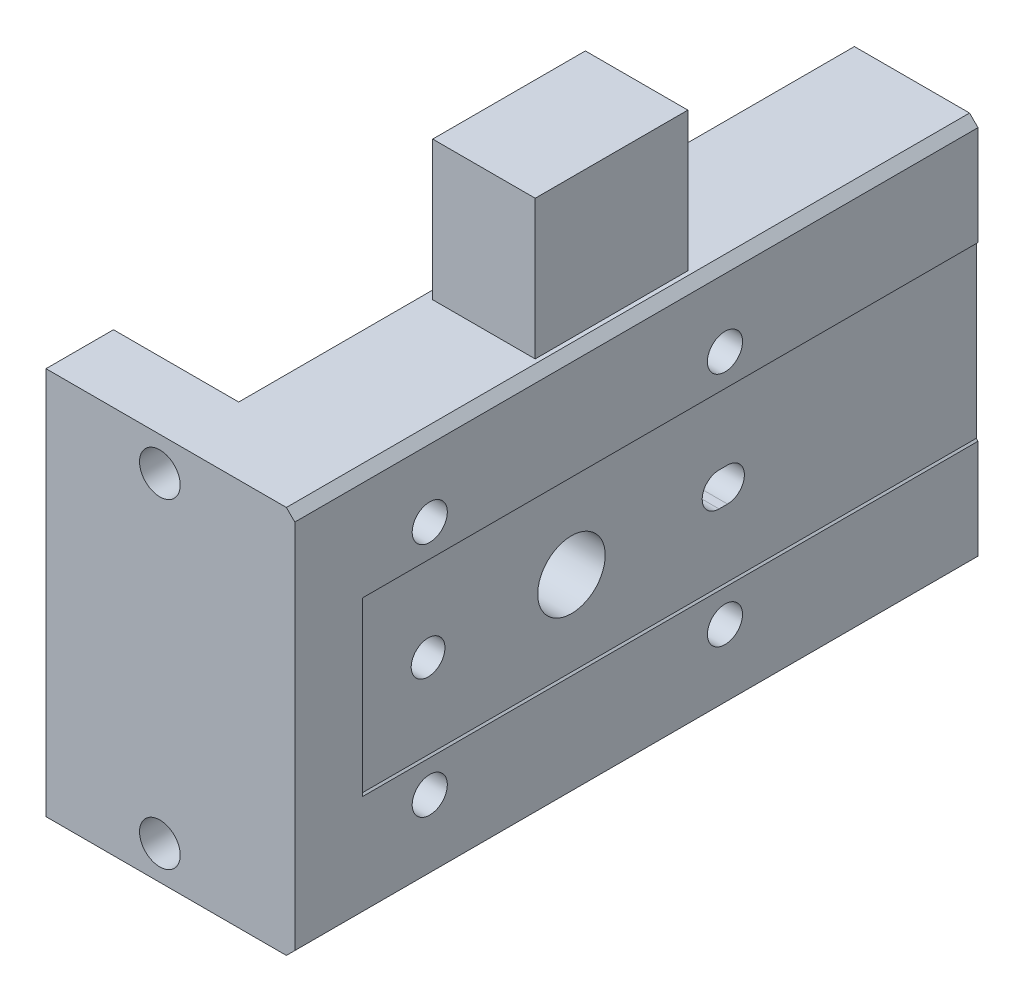
SolidWorks part; units mm, degrees
ref_plane "Front" through (0, 0, 0) normal (0, 0, 1) x (1, 0, 0)
ref_plane "Top" through (0, 0, 0) normal (0, 1, 0) x (1, 0, 0)
ref_plane "Right" through (0, 0, 0) normal (1, 0, 0) x (0, 0, -1)
sketch "Sketch1" plane through (0, 0, -1048.9574) normal (0, 0, 1) x (1, 0, 0)
  line L0 (8.0391, 23) -> (-8.0391, 23) construction
  line L1 (-6.1741, 23) -> (23.3259, 23)
  line L2 (-6.1741, 23) -> (-6.1741, -23)
  line L3 (-6.1741, -23) -> (23.3259, -23)
  line L4 (23.3259, 23) -> (23.3259, 10.2)
  line L5 (-6.1741, 0) -> (23.1259, 0) construction
  line L6 (-8.6741, 22.365) -> (-8.6741, 8.135) construction
  line L8 (-1.4859, -23) -> (1.4859, -23) construction
  line L9 (23.1259, 10) -> (23.1259, -10)
  line L10 (23.1259, -10) -> (23.3259, -10.2)
  line L11 (23.1259, 10) -> (23.3259, 10.2)
  line L12 (23.3259, -10.2) -> (23.3259, -23)
  dimension "D1" = 2.5
  dimension "D2" = 32
  dimension "D3" = 45
  dimension "D4" = 0.2
  dimension "D5" = 20
extrude "Base-Extrude" add sketch "Sketch1" along normal up to surface (8 mm away)
sketch "Sketch3" plane through (0, 0, -1048.9574) normal (0, 0, -1) x (-1, 0, 0)
  line L0 (-23.3259, 10.2) -> (-23.3259, 23) construction
  line L1 (-23.3259, 23) -> (6.1741, 23) construction
  line L2 (-23.3259, 10.2) -> (-23.3259, 23)
  line L3 (-23.3259, 23) -> (-8.6741, 23)
  line L4 (6.1741, -23) -> (-23.3259, -23) construction
  line L5 (-23.3259, -23) -> (-23.3259, -10.2) construction
  line L6 (-23.3259, -10.2) -> (-23.1259, -10) construction
  line L7 (-23.1259, -10) -> (-23.1259, 10) construction
  line L8 (-23.1259, 10) -> (-23.3259, 10.2) construction
  line L9 (-8.6741, -23) -> (-23.3259, -23)
  line L10 (-23.3259, -23) -> (-23.3259, -10.2)
  line L11 (-23.3259, -10.2) -> (-23.1259, -10)
  line L12 (-23.1259, -10) -> (-23.1259, 10)
  line L13 (-23.1259, 10) -> (-23.3259, 10.2)
  line L14 (-8.6741, -8.135) -> (-8.6741, -22.365) construction
  line L19 (-8.6741, 23) -> (-8.6741, -23)
extrude "Boss-Extrude1" add sketch "Sketch3" along normal up to surface (73 mm away)
sketch "Sketch15" plane through (0, 0, -1040.9574) normal (0, 0, 1) x (1, 0, 0)
  line L0 (23.1259, -10) -> (23.1259, 10) construction
  line L1 (23.1259, -10) -> (23.1259, 10)
  line L2 (23.3259, -10.2) -> (23.1259, -10) construction
  line L3 (23.1259, 10) -> (23.3259, 10.2) construction
  line L4 (23.3259, -10.2) -> (23.1259, -10)
  line L5 (23.1259, 10) -> (23.3259, 10.2)
  line L6 (23.3259, -10.2) -> (23.3259, 10.2)
extrude "Boss-Extrude3" add sketch "Sketch15" against normal up to surface (8 mm away) up to face at (1.25, -5.75, -1048.9574)
hole_wizard "8.0 Diameter Hole1" positions "Sketch5" profile "Sketch4" hole size "M8.0" standard "Ansi Metric" end condition through all
sketch "Sketch5" plane through (23.1259, 0, 0) normal (1, 0, 0) x (0, 0, -1)
  point P0 (1073.9574, 0)
sketch "Sketch4" plane through (23.1259, 0, -1073.9574) normal (0, 1, 0) x (0, 0, -1)
  line L0 (0, 0) -> (0, 29.3)
  line L1 (0, 29.3) -> (4, 29.3)
  line L2 (4, 29.3) -> (4, 0)
  line L5 (4, 0) -> (0, 0)
  line L11 (0, -6.35) -> (0, 107.95) construction
  dimension "Thru Hole Dia." = 8
  dimension "Thru Hole Depth" = 29.3
hole_wizard "#8-32 Tapped Hole1" positions "Sketch7" profile "Sketch6" tap size "#8-32" standard "Ansi Inch"
sketch "Sketch7" plane through (23.3259, 0, 0) normal (1, 0, 0) x (0, 0, -1)
  point P0 (1056.9574, 14)
  point P1 (1091.9574, 14)
  point P3 (1056.9574, -14)
  point P4 (1091.9574, -14)
sketch "Sketch6" plane through (23.3259, 14, -1056.9574) normal (0, 1, 0) x (0, 0, -1)
  line L0 (0, 0) -> (0, 13.3314)
  line L1 (0, 13.3314) -> (1.7272, 12.2936)
  line L2 (1.7272, 12.2936) -> (1.7272, 8.3312)
  line L3 (1.7272, 8.3312) -> (2.0828, 8.3312)
  line L4 (2.0828, 8.3312) -> (2.0828, 0)
  line L5 (2.0828, 0) -> (0, 0)
  line L10 (0, 13.3314) -> (-1.7272, 12.2936) construction
  line L11 (0, -6.35) -> (0, 107.95) construction
  dimension "Tap Drill Dia." = 3.4544
  dimension "Tap Drill Depth" = 12.2936
  dimension "Thread Dia." = 4.1656
  dimension "Thread Depth" = 8.3312
  dimension "Drill Angle" = 118
hole_wizard "#10-32 Tapped Hole1" positions "Sketch10" profile "Sketch9" tap size "#10-32" standard "Ansi Inch" end condition through all
sketch "Sketch10" plane through (0, 0, -1040.9574) normal (0, 0, 1) x (1, 0, 0)
  line L0 (-8.6741, 22.365) -> (-8.6741, 8.135) construction
  line L1 (-8.0391, 0) -> (7.3259, 0) construction
  line L2 (-8.0391, 7.5) -> (-8.0391, -7.5) construction
  point P0 (7.3259, 19)
  point P1 (7.3259, -19)
  dimension "D1" = 16
  dimension "D2" = 38
sketch "Sketch9" plane through (7.3259, 19, -1040.9574) normal (1, 0, 0) x (0, -1, 0)
  line L0 (0, 0) -> (0, 81)
  line L1 (0, 81) -> (2.413, 81)
  line L2 (2.413, 81) -> (2.413, 0)
  line L5 (2.413, 0) -> (0, 0)
  line L11 (0, -6.35) -> (0, 107.95) construction
  dimension "Thru Hole Dia." = 4.826
  dimension "Thru Hole Depth" = 81
sketch "Sketch11" plane through (23.1259, 0, 0) normal (1, 0, 0) x (0, 0, -1)
  line L0 (1091.9574, 14) -> (1091.9574, 0) construction
  line L2 (1040.9574, 0) -> (1121.9574, 0) construction
  line L4 (1094.4574, 0) -> (1094.4574, 14) construction
  line L5 (1089.4574, 0) -> (1089.4574, 14) construction
  line L6 (1091.4574, 2) -> (1092.4574, 2)
  line L7 (1091.4574, -2) -> (1092.4574, -2)
  arc A0 (1092.4574, -2) -> (1092.4574, 2) centre (1092.4574, 0) ccw
  arc A1 (1091.4574, 2) -> (1091.4574, -2) centre (1091.4574, 0) ccw
  dimension "D1" = 4
  dimension "D2" = 5
extrude "Cut-Extrude1" cut sketch "Sketch11" against normal blind 3.5
hole_wizard "Hole1" positions "Sketch13" profile "Sketch12" legacy
sketch "Sketch13" plane through (23.1259, 0, 0) normal (1, 0, 0) x (0, 0, -1)
  line L0 (1040.9574, 0) -> (1121.9574, 0) construction
  point P0 (1056.9574, 0)
sketch "Sketch12" plane through (23.1259, 0, -1056.9574) normal (0, 1, 0) x (0, 0, -1)
  line L0 (0, 0) -> (0, 3.5)
  line L1 (0, 3.5) -> (2, 3.5)
  line L2 (2, 3.5) -> (2, 0)
  line L3 (2, 0) -> (0, 0)
  line L4 (0, 110) -> (0, -10) construction
  dimension "Diameter" = 4
  dimension "Depth" = 3.5
sketch "Sketch2" plane through (0, 0, -1040.9574) normal (0, 0, 1) x (1, 0, 0)
  line L0 (23.3259, -23) -> (23.3259, 23) construction
  circle A2 centre (0, 10.5156) radius 2
  circle A3 centre (0, -11.0744) radius 2
  circle A4 centre (15.3259, 17.5) radius 3
  circle A5 centre (15.3259, -17.5) radius 3
  dimension "D1" = 6
  dimension "D4" = 4
  dimension "D3" = 8
sketch "Sketch14" plane through (0, 23, 0) normal (0, 1, 0) x (-1, 0, 0)
  line L1 (-21.8259, -1070.9574) -> (-9.6741, -1070.9574)
  line L2 (-21.8259, -1070.9574) -> (-21.8259, -1089.0574)
  line L3 (-21.8259, -1089.0574) -> (-9.6741, -1089.0574)
  line L4 (-9.6741, -1070.9574) -> (-9.6741, -1089.0574)
  line L5 (-23.3259, -1040.9574) -> (-23.3259, -1121.9574) construction
  line L6 (-8.6741, -1121.9574) -> (-8.6741, -1048.9574) construction
  line L7 (-8.925, -1070.9574) -> (8.925, -1070.9574) construction
  dimension "D1" = 18.1
  dimension "D3" = 1.5
  dimension "D4" = 1
extrude "Boss-Extrude2" add sketch "Sketch14" along normal blind 16.5
chamfer "Chamfer1" distance 1 angle 45 2 edges at (23.3259, 23, -1081.4574) (23.3259, -23, -1081.4574)
